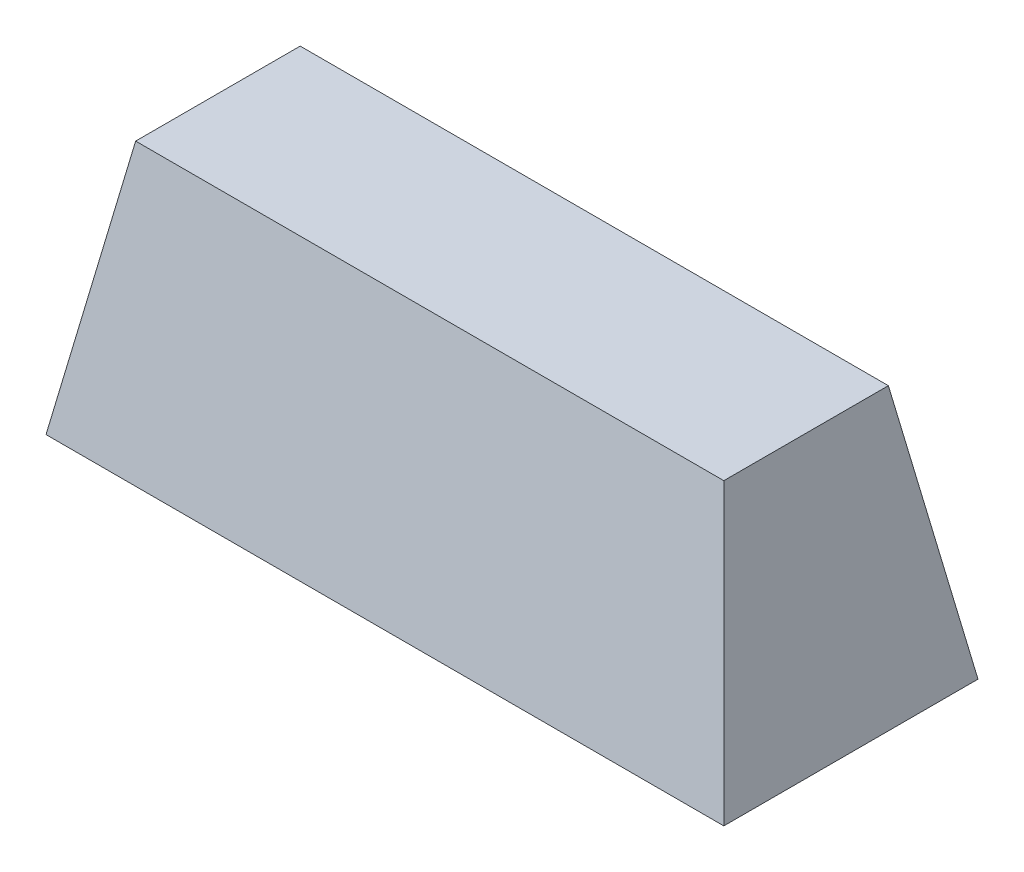
SolidWorks part; units mm, degrees
ref_plane "Front Plane" through (0, 0, 0) normal (0, 0, 1) x (1, 0, 0)
ref_plane "Top Plane" through (0, 0, 0) normal (0, 1, 0) x (1, 0, 0)
ref_plane "Right Plane" through (0, 0, 0) normal (1, 0, 0) x (0, 0, -1)
sketch "Sketch1" plane through (0, 0, 0) normal (0, 1, 0) x (1, 0, 0)
  line L1 (100, 37.5) -> (-100, 37.5)
  line L2 (100, 37.5) -> (100, -37.5)
  line L3 (100, -37.5) -> (-100, -37.5)
  line L4 (-100, 37.5) -> (-100, -37.5)
  line L5 (100, 37.5) -> (-100, -37.5) construction
  line L6 (100, -37.5) -> (-100, 37.5) construction
  point P0 (0, 0)
  dimension "D1" = 75
  dimension "D2" = 200
extrude "Boss-Extrude1" add sketch "Sketch1" along normal blind 75 draft 10
equation "\"case_height\"= 100mm"
equation "\"case_length\"= 700mm"
equation "\"clock_width\"= 75mm"
equation "\"clock_length\"= 200mm"
equation "\"clock_height\"= 75mm"
equation "\"arm_sleeve_diameter\"= 100mm"
equation "\"square_length\"= 50mm"
equation "\"board_length\"= \"square_length\" * 8"
equation "\"clock_offset\"= 10mm"
equation "\"D1@Sketch1\"=\"clock_width\""
equation "\"D2@Sketch1\"=\"clock_length\""
equation "\"D1@Boss-Extrude1\"=\"clock_height\""
